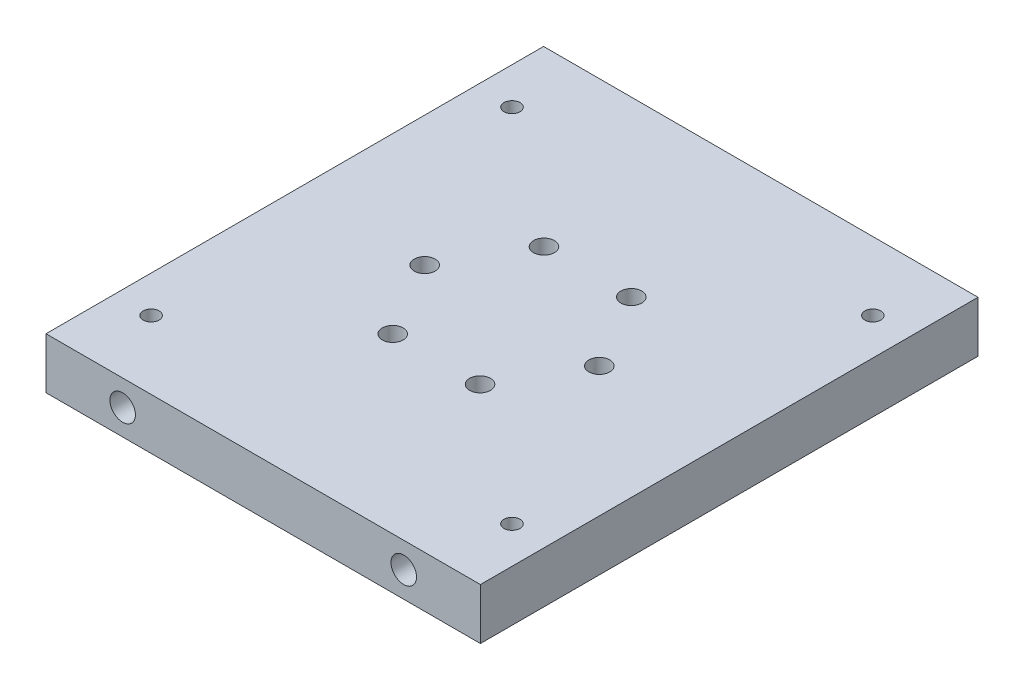
SolidWorks part; units mm, degrees
material "6061-T6 (SS)"
ref_plane "Front Plane" through (0, 0, 0) normal (0, 0, 1) x (1, 0, 0)
ref_plane "Top Plane" through (0, 0, 0) normal (0, 1, 0) x (1, 0, 0)
ref_plane "Right Plane" through (0, 0, 0) normal (1, 0, 0) x (0, 0, -1)
sketch "Sketch1" plane through (0, 0, 0) normal (0, 0, 1) x (1, 0, 0)
  line L1 (0, 0) -> (107.95, 0)
  line L2 (0, 0) -> (0, -12.7)
  line L3 (0, -12.7) -> (107.95, -12.7)
  line L4 (107.95, 0) -> (107.95, -12.7)
  line L5 (0, 0) -> (107.95, -12.7) construction
  line L6 (0, -12.7) -> (107.95, 0) construction
  point P5 (53.975, -6.35)
  dimension "D1" = 12.7
  dimension "D2" = 107.95
extrude "Boss-Extrude1" add sketch "Sketch1" along normal blind 123.65
sketch "Sketch2" plane through (0, 0, 123.65) normal (0, 0, 1) x (1, 0, 0)
  line L0 (0, -6.35) -> (107.95, -6.35) construction
  line L1 (0, 0) -> (0, -12.7) construction
  line L2 (107.95, -12.7) -> (107.95, 0) construction
  circle A0 centre (19.05, -6.35) radius 3.175
  circle A1 centre (88.9, -6.35) radius 3.175
  dimension "D1" = 6.35
  dimension "D2" = 6.35
  dimension "D3" = 19.05
  dimension "D4" = 19.05
extrude "Cut-Extrude1" cut sketch "Sketch2" against normal blind 25.4
ref_plane "Plane1" through (0, 0, 61.825) normal (0, 0, 1) x (1, 0, 0)
mirror "Mirror1" about plane through (0, 0, 61.825) normal (0, 0, 1) of "Cut-Extrude1"
sketch "Sketch4" plane through (0, 0, 0) normal (0, 1, 0) x (1, 0, 0)
  line L0 (0, -123.65) -> (0, 0) construction
  line L2 (107.95, -123.65) -> (0, -123.65) construction
  line L3 (107.95, -123.65) -> (107.95, 0) construction
  line L4 (107.95, 0) -> (0, 0) construction
  circle A0 centre (9.135, -106.665) radius 1.985
  circle A1 centre (9.14, -16.99) radius 1.985
  circle A2 centre (98.81, -106.665) radius 1.985
  circle A3 centre (98.815, -16.99) radius 1.985
  dimension "D1" = 9.135
  dimension "D2" = 3.97
  dimension "D3" = 16.985
  dimension "D4" = 3.97
  dimension "D5" = 3.97
  dimension "D6" = 3.97
  dimension "D7" = 9.14
  dimension "D8" = 16.985
  dimension "D9" = 9.135
  dimension "D10" = 16.99
  dimension "D11" = 9.14
  dimension "D12" = 16.99
extrude "Cut-Extrude3" cut sketch "Sketch4" against normal through all contours A3 | A2 | A0 | A1
sketch "Sketch6" plane through (0, 0, 0) normal (0, 1, 0) x (1, 0, 0)
  line L0 (107.95, 0) -> (0, 0) construction
  line L1 (107.95, -123.65) -> (107.95, 0) construction
  line L2 (25.575, -61.825) -> (38.975, -61.825) construction
  circle A0 centre (53.975, -61.825) radius 28.4 construction
  circle A2 centre (53.975, -61.825) radius 15 construction
  circle A3 centre (32.275, -61.825) radius 2.6
  circle A4 centre (43.125, -43.0322) radius 2.6
  circle A5 centre (64.825, -43.0322) radius 2.6
  circle A6 centre (75.675, -61.825) radius 2.6
  circle A7 centre (64.825, -80.6178) radius 2.6
  circle A8 centre (43.125, -80.6178) radius 2.6
  dimension "D1" = 56.8
  dimension "D4" = 30
  dimension "D5" = 5.2
  dimension "D6" = 6
  dimension "D2" = 61.825
  dimension "D3" = 53.975
extrude "Cut-Extrude8" cut sketch "Sketch6" against normal through all
